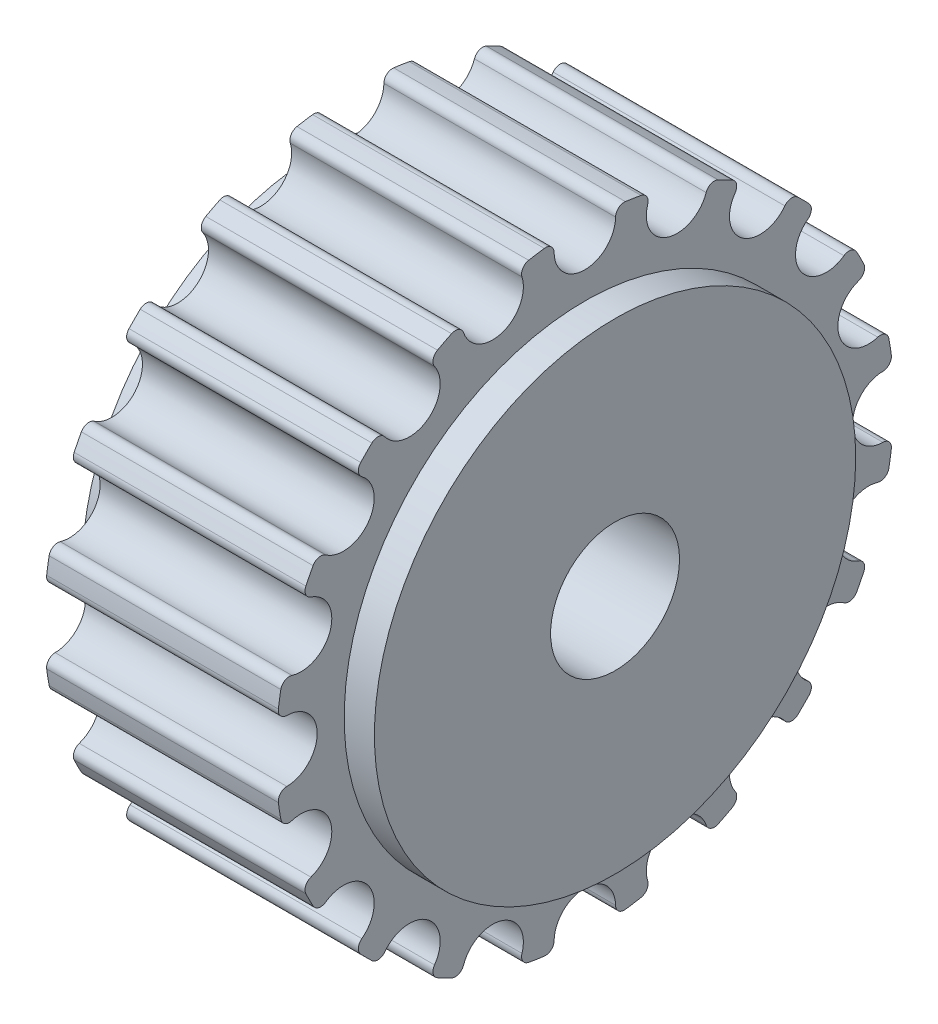
SolidWorks part; units mm, degrees
ref_plane "Front" through (0, 0, 0) normal (0, 0, 1) x (1, 0, 0)
ref_plane "Top" through (0, 0, 0) normal (0, 1, 0) x (1, 0, 0)
ref_plane "Right" through (0, 0, 0) normal (1, 0, 0) x (0, 0, -1)
sketch "Sketch1" plane through (0, 0, 0) normal (1, 0, 0) x (0, 0, -1)
  line L0 (0, 14.81) -> (0, 0) construction
  line L1 (0, 0) -> (4.5765, 14.0851) construction
  line L2 (0, 13.285) -> (0, 0)
  line L3 (0, 0) -> (4.1053, 12.6348)
  circle A0 centre (0, 0) radius 13.285 construction
  circle A1 centre (0, 0) radius 15.345 construction
  circle A2 centre (0, 14.81) radius 1.525 construction
  circle A3 centre (1.9549, 14.7863) radius 0.43 construction
  circle A4 centre (4.5765, 14.0851) radius 1.525 construction
  circle A5 centre (2.7101, 14.6667) radius 0.43 construction
  arc A6 (0, 13.285) -> (1.5249, 14.7915) centre (0, 14.81) ccw
  arc A7 (2.0112, 15.2126) -> (1.5249, 14.7915) centre (1.9549, 14.7863) ccw
  arc A8 (2.7882, 15.0896) -> (2.0112, 15.2126) centre (0, 0) ccw
  arc A9 (3.1206, 14.5388) -> (2.7882, 15.0896) centre (2.7101, 14.6667) ccw
  arc A10 (3.1206, 14.5388) -> (4.1053, 12.6348) centre (4.5765, 14.0851) ccw
  dimension "D1" = 2.06
  dimension "D2" = 30.69
  dimension "D3" = 3.05
  dimension "D4" = 0.86
  dimension "D5" = 18
extrude "Boss-Extrude1" add sketch "Sketch1" along normal mid plane 11.5
pattern_circular "CirPattern1" count 20 over 360 about axis through (0, 0, 0) along (1, 0, 0) of "Boss-Extrude1"
sketch "Sketch2" plane through (5.75, 0, 0) normal (1, 0, 0) x (0, 0, -1)
  circle A0 centre (0, 0) radius 11.945
  arc A1 (2.7882, 15.0896) -> (2.0112, 15.2126) centre (0, 0) ccw construction
  dimension "D1" = 3.4
extrude "Boss-Extrude2" add sketch "Sketch2" along normal blind 1.5
mirror "Mirror1" about plane through (0, 0, 0) normal (1, 0, 0) of "Boss-Extrude2"
sketch "Sketch3" plane through (7.25, 0, 0) normal (1, 0, 0) x (0, 0, -1)
  circle A0 centre (0, 0) radius 3.2
  dimension "D1" = 6.4
extrude "Cut-Extrude1" cut sketch "Sketch3" against normal up to surface (14.5 mm away) up to face at (-7.25, 0, -11.945)
equation "\"D2\"=26.57"
